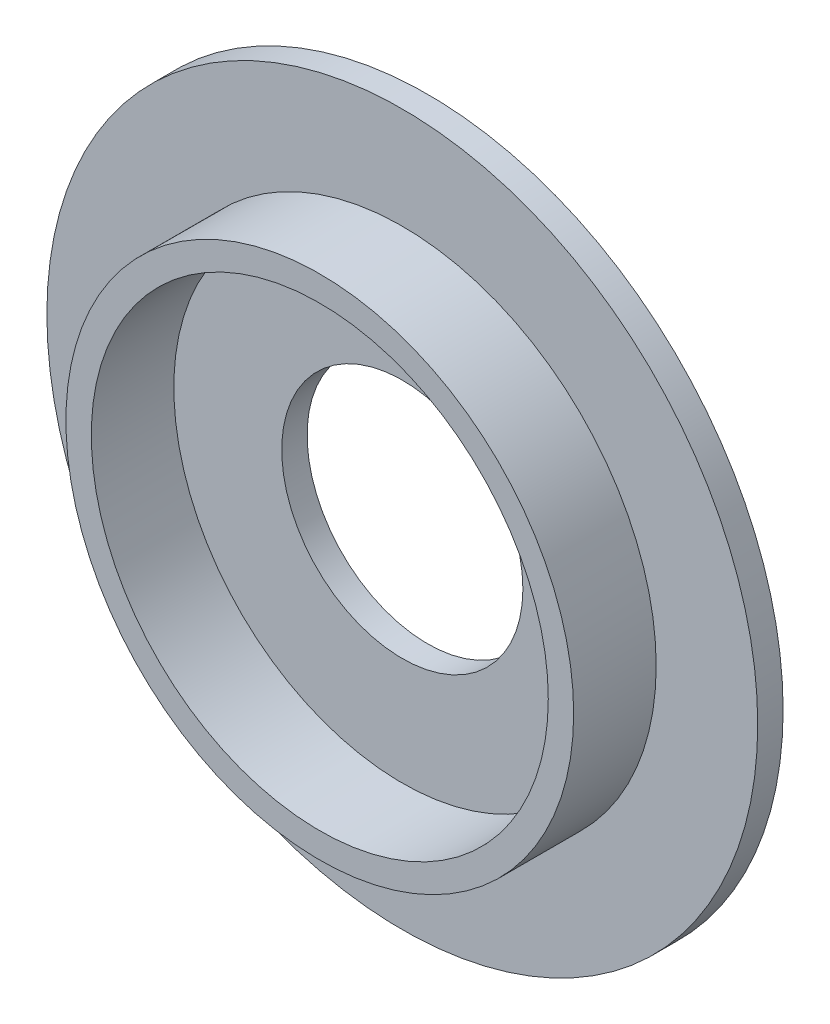
SolidWorks part; units mm, degrees
ref_plane "前视" through (0, 0, 0) normal (0, 0, 1) x (1, 0, 0)
ref_plane "上视" through (0, 0, 0) normal (0, 1, 0) x (1, 0, 0)
ref_plane "右视" through (0, 0, 0) normal (1, 0, 0) x (0, 0, -1)
sketch "草图1" plane through (0, 0, 0) normal (0, 0, 1) x (1, 0, 0)
  line L0 (0, 155.7418) -> (0, -151.0312) construction
  line L1 (155.2911, 0) -> (-154.426, 0) construction
  circle A0 centre (0, 0) radius 140
  circle A1 centre (0, 0) radius 47.5
  dimension "D1" = 95
  dimension "D2" = 280
extrude "拉伸1" add sketch "草图1" along normal blind 10
sketch "草图2" plane through (0, 0, 10) normal (0, 0, 1) x (1, 0, 0)
  circle A0 centre (0, 0) radius 100
  circle A1 centre (0, 0) radius 90
  dimension "D1" = 180
  dimension "D2" = 200
extrude "拉伸2" add sketch "草图2" along normal blind 32.5
